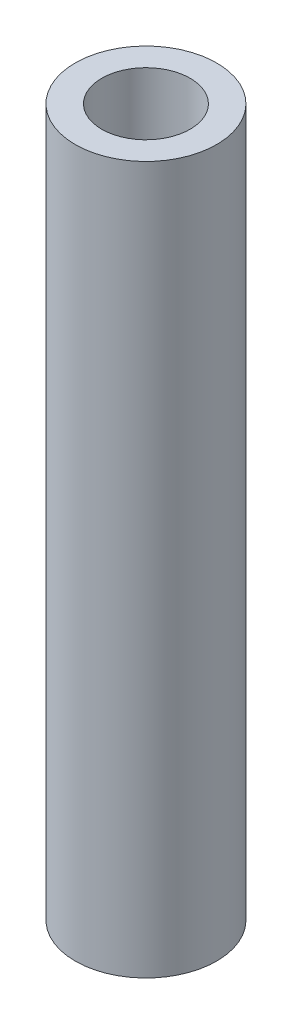
SolidWorks part; units mm, degrees
material "6061 合金"
ref_plane "前视基准面" through (0, 0, 0) normal (0, 0, 1) x (1, 0, 0)
ref_plane "上视基准面" through (0, 0, 0) normal (0, 1, 0) x (1, 0, 0)
ref_plane "右视基准面" through (0, 0, 0) normal (1, 0, 0) x (0, 0, -1)
sketch "草图1" plane through (0, 0, 0) normal (0, 1, 0) x (1, 0, 0)
  circle A0 centre (0, 0) radius 1.25
  circle A1 centre (0, 0) radius 2
  dimension "D1" = 2.5
  dimension "D2" = 4
extrude "凸台-拉伸1" add sketch "草图1" along normal blind 20
